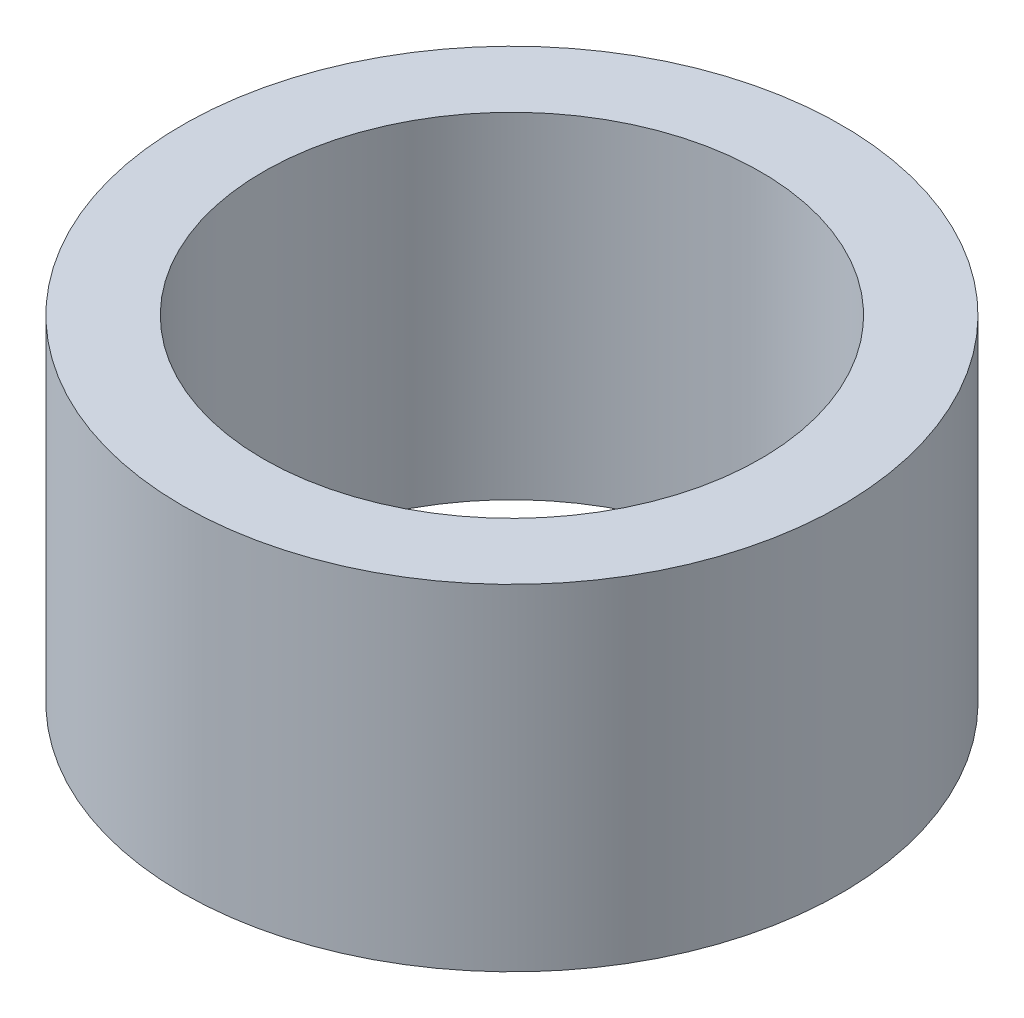
SolidWorks part; units mm, degrees
ref_plane "Front Plane" through (0, 0, 0) normal (0, 0, 1) x (1, 0, 0)
ref_plane "Top Plane" through (0, 0, 0) normal (0, 1, 0) x (1, 0, 0)
ref_plane "Right Plane" through (0, 0, 0) normal (1, 0, 0) x (0, 0, -1)
sketch "Sketch1" plane through (0, 0, 0) normal (0, 1, 0) x (1, 0, 0)
  circle A0 centre (0, 0) radius 5.5
  circle A1 centre (0, 0) radius 4.15
extrude "Boss-Extrude1" add sketch "Sketch1" along normal blind 5.6
